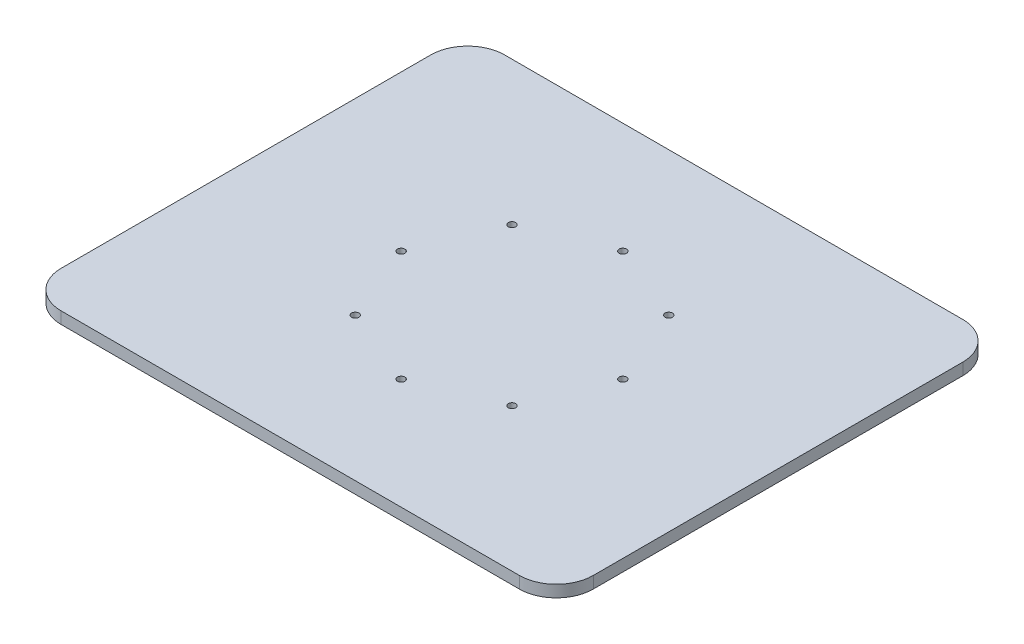
SolidWorks part; units mm, degrees
ref_plane "前视基准面" through (0, 0, 0) normal (0, 0, 1) x (1, 0, 0)
ref_plane "上视基准面" through (0, 0, 0) normal (0, 1, 0) x (1, 0, 0)
ref_plane "右视基准面" through (0, 0, 0) normal (1, 0, 0) x (0, 0, -1)
other "Configuration Table"
ref_plane "基准面1" through (0, 16, 0) normal (0, 1, 0) x (1, 0, 0)
sketch "草图1" plane through (0, 16, 0) normal (0, 1, 0) x (1, 0, 0)
  line L0 (-360, -300) -> (360, -300)
  line L1 (360, -300) -> (360, 300)
  line L2 (360, 300) -> (-360, 300)
  line L3 (-360, 300) -> (-360, -300)
extrude "凸台-拉伸1" add sketch "草图1" against normal blind 16
hole_wizard "M5 六角头螺栓的柱形沉头孔1" positions "草图5" profile "草图4" counterbore size "M5" standard "ANSI Metric"
sketch "草图5" plane through (0, 16, 0) normal (0, 1, 0) x (1, 0, 0)
  point P0 (106.066, -106.066)
  point P1 (0, -150)
  point P2 (-106.066, -106.066)
  point P3 (-150, 0)
  point P4 (-106.066, 106.066)
  point P5 (0, 150)
  point P6 (106.066, 106.066)
  point P7 (150, 0)
sketch "草图4" plane through (106.066, 16, 106.066) normal (1, 0, 0) x (0, 0, 1)
  line L0 (0, 0) -> (0, 16)
  line L1 (0, 16) -> (2.75, 16)
  line L3 (2.75, 16) -> (2.75, 12)
  line L4 (2.75, 12) -> (5, 12)
  line L5 (5, 12) -> (5, 0)
  line L7 (5, 0) -> (0, 0)
  line L11 (0, -6.35) -> (0, 107.95) construction
  dimension "通孔孔直径" = 5.5
  dimension "通孔孔深度" = 16
  dimension "柱形沉头孔直径" = 10
  dimension "柱形沉头孔深度" = 12
fillet "圆角1" radius 50 4 edges at (360, 8, -300) (360, 8, 300) (-360, 8, 300) (-360, 8, -300)
